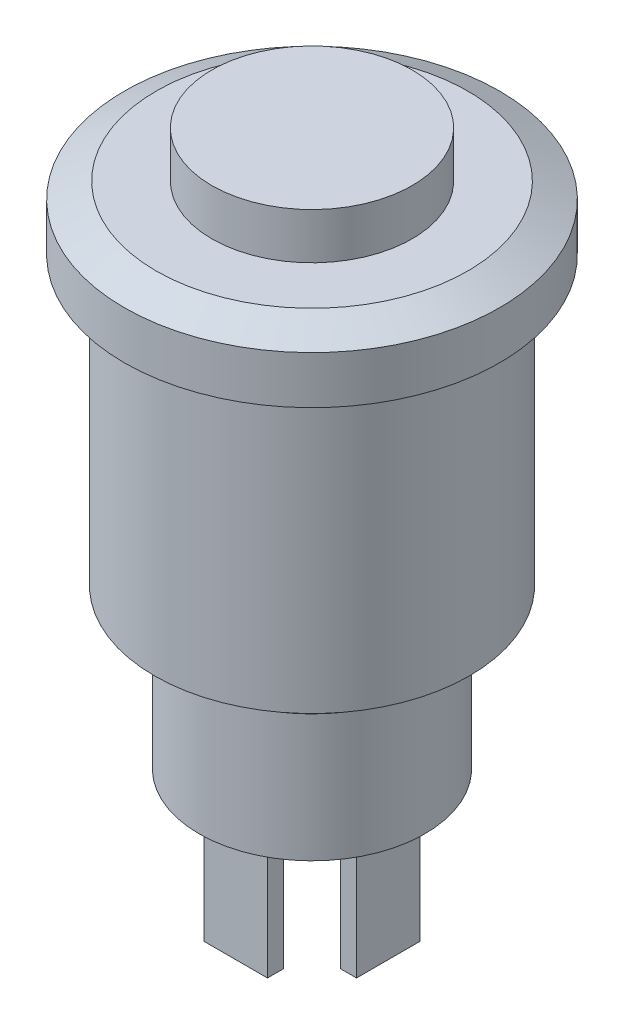
SolidWorks part; units mm, degrees
ref_plane "Plan de face" through (0, 0, 0) normal (0, 0, 1) x (1, 0, 0)
ref_plane "Plan de dessus" through (0, 0, 0) normal (0, 1, 0) x (1, 0, 0)
ref_plane "Plan de droite" through (0, 0, 0) normal (1, 0, 0) x (0, 0, -1)
ref_axis "Axe1" through (0, 55, 0) along (0, -1, 0)
sketch "Esquisse1" plane through (0, 0, 0) normal (0, 0, 1) x (1, 0, 0)
  line L0 (0, 3.45) -> (-3.15, 3.45)
  line L1 (0, 55) -> (0, -55) construction
  line L2 (-3.15, 3.45) -> (-3.15, 2)
  line L3 (-3.15, 2) -> (-4.9, 2)
  line L4 (-4.9, 2) -> (-5.9, 1.5)
  line L5 (-5.9, 1.5) -> (-5.9, 0)
  line L6 (-5.9, 0) -> (-4.95, 0)
  line L7 (-4.95, 0) -> (-4.95, -9)
  line L8 (-4.95, -9) -> (-3.55, -10)
  line L9 (-3.55, -10) -> (-3.55, -14)
  line L10 (-3.55, -14) -> (0, -14)
  line L11 (0, -14) -> (0, 3.45)
  point P13 (-11.8, 1.2042)
  dimension "D1" = 3.15
  dimension "D2" = 1.45
  dimension "D3" = 5.9
  dimension "D4" = 9
  dimension "D5" = 5
  dimension "D6" = 4.95
  dimension "D7" = 1
  dimension "D8" = 3.55
  dimension "D9" = 2
  dimension "D10" = 0.5
  dimension "D11" = 1
revolve "Révolution1" add sketch "Esquisse1" angle 360 about axis through (0, 55, 0) along (0, -1, 0)
sketch "Esquisse2" plane through (0, -14, 0) normal (0, -1, 0) x (1, 0, 0)
  line L1 (-1, 2.4) -> (1, 2.4)
  line L2 (-1, 2.4) -> (-1, 1.9)
  line L3 (-1, 1.9) -> (1, 1.9)
  line L4 (1, 2.4) -> (1, 1.9)
  point P4 (0, 1.9)
  dimension "D1" = 0.5
  dimension "D2" = 2
  dimension "D3" = 1.9
extrude "Boss.-Extru.1" add sketch "Esquisse2" along normal blind 4
pattern_circular "Répétition circulaire1" count 4 over 360 about axis through (0, 0, 0) along (0, 1, 0) of "Boss.-Extru.1"
